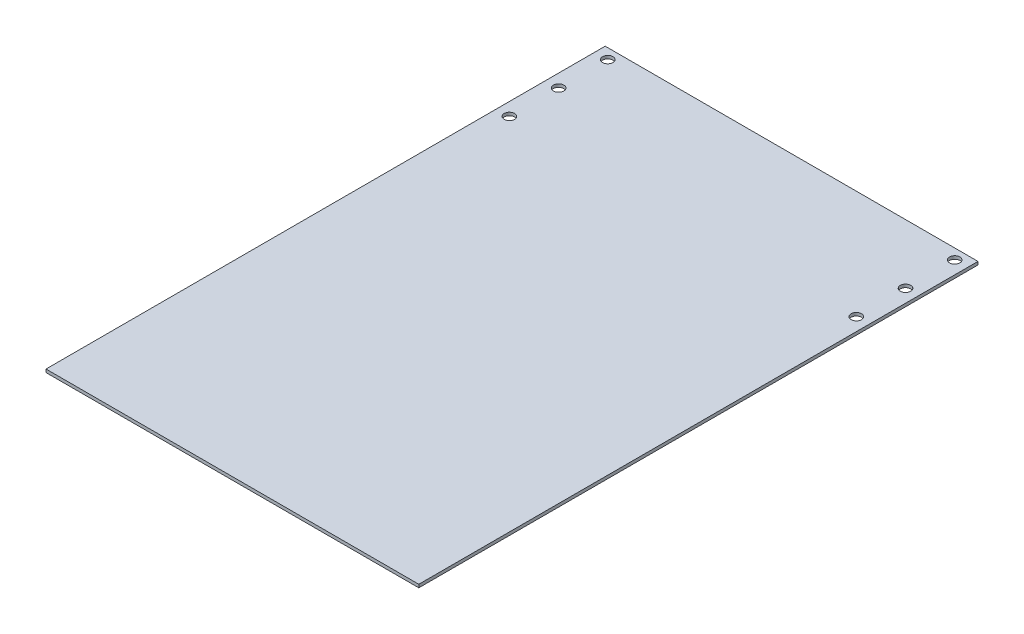
SolidWorks part; units mm, degrees
ref_plane "Front Plane" through (0, 0, 0) normal (0, 0, 1) x (1, 0, 0)
ref_plane "Top Plane" through (0, 0, 0) normal (0, 1, 0) x (1, 0, 0)
ref_plane "Right Plane" through (0, 0, 0) normal (1, 0, 0) x (0, 0, -1)
sketch "Sketch1" plane through (0, 0, 0) normal (0, 1, 0) x (1, 0, 0)
  line L1 (-180, -270) -> (180, -270)
  line L2 (-180, -270) -> (-180, 270)
  line L3 (-180, 270) -> (180, 270)
  line L4 (180, -270) -> (180, 270)
  line L5 (-180, -270) -> (180, 270) construction
  line L6 (-180, 270) -> (180, -270) construction
  point P0 (0, 0)
extrude "Boss-Extrude1" add sketch "Sketch1" along normal blind 3
sketch "Sketch2" plane through (0, 3, 0) normal (0, 1, 0) x (1, 0, 0)
  line L0 (0, 321.1416) -> (0, -329.482) construction
  line L1 (-249.6352, 0) -> (323.1784, 0) construction
  line L2 (-167.5, 274.9465) -> (-167.5, 128.6129) construction
  line L7 (-193.9765, 212.5) -> (-141.5585, 212.5) construction
  line L8 (193.9765, 212.5) -> (141.5585, 212.5) construction
  line L9 (167.5, 274.9465) -> (167.5, 128.6129) construction
  line L10 (-180, 270) -> (-180, -270) construction
  line L11 (180, 270) -> (-180, 270) construction
  circle A0 centre (-167.5, 212.5) radius 5
  circle A2 centre (-167.5, 165) radius 5
  circle A3 centre (-167.5, 260) radius 5
  circle A4 centre (167.5, 260) radius 5
  circle A5 centre (167.5, 165) radius 5
  circle A6 centre (167.5, 212.5) radius 5
  point P14 (-167.5, 212.5)
  point P27 (167.5, 212.5)
  dimension "D3" = 57.5
  dimension "D1" = 12.5
  dimension "D2" = 12.5
  dimension "D4" = 47.5
extrude "Cut-Extrude1" cut sketch "Sketch2" against normal through all both and the other way through all
